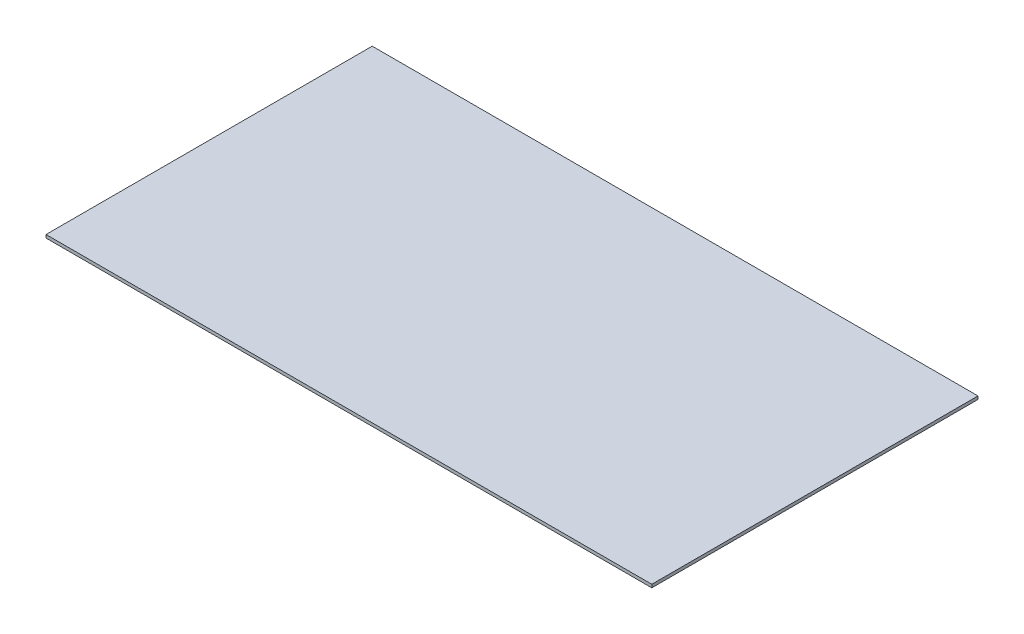
SolidWorks part; units mm, degrees
ref_plane "Front Plane" through (0, 0, 0) normal (0, 0, 1) x (1, 0, 0)
ref_plane "Top Plane" through (0, 0, 0) normal (0, 1, 0) x (1, 0, 0)
ref_plane "Right Plane" through (0, 0, 0) normal (1, 0, 0) x (0, 0, -1)
sketch "Sketch1" plane through (0, 0, 0) normal (1, 0, 0) x (0, 0, -1)
  line L1 (-525, -5) -> (525, -5)
  line L2 (-525, -5) -> (-525, 5)
  line L3 (-525, 5) -> (525, 5)
  line L4 (525, -5) -> (525, 5)
  line L5 (-525, -5) -> (525, 5) construction
  line L6 (-525, 5) -> (525, -5) construction
  point P0 (0, 0)
  dimension "D1" = 1050
  dimension "D2" = 10
extrude "Boss-Extrude1" add sketch "Sketch1" along normal blind 1950
